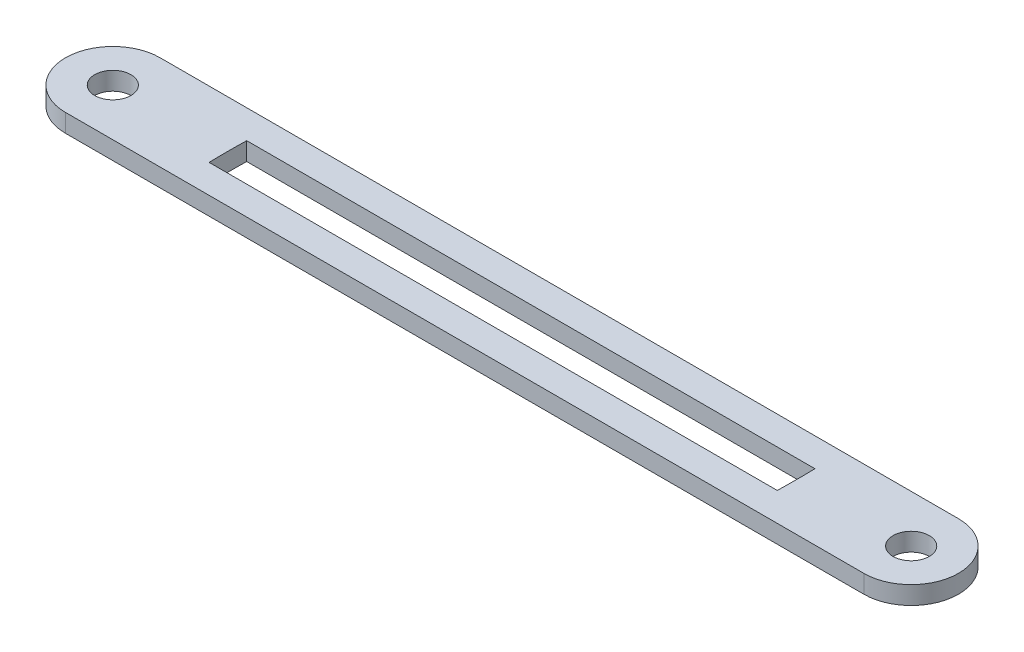
SolidWorks part; units mm, degrees
material "6061-T6 (SS)"
ref_plane "Front Plane" through (0, 0, 0) normal (0, 0, 1) x (1, 0, 0)
ref_plane "Top Plane" through (0, 0, 0) normal (0, 1, 0) x (1, 0, 0)
ref_plane "Right Plane" through (0, 0, 0) normal (1, 0, 0) x (0, 0, -1)
sketch "Sketch1" plane through (0, 0, 0) normal (0, 1, 0) x (1, 0, 0)
  line L0 (-35, 0) -> (35, 0) construction
  line L1 (35, 4.15) -> (-35, 4.15)
  line L3 (-35, -4.15) -> (35, -4.15)
  line L4 (24.9073, -1.65) -> (-24.9073, -1.65)
  line L5 (-24.9073, 1.65) -> (24.9073, 1.65)
  line L6 (35, 1.65) -> (-35, 1.65) construction
  line L7 (-35, -1.65) -> (35, -1.65) construction
  circle A0 centre (35, 0) radius 1.5875
  circle A1 centre (-35, 0) radius 1.5875
  arc A2 (-35, 4.15) -> (-35, -4.15) centre (-35, 0) ccw
  arc A3 (35, -4.15) -> (35, 4.15) centre (35, 0) ccw
  circle A4 centre (-9.4564, 0) radius 0.5953 construction
  circle A5 centre (-4.9564, 0) radius 0.5953 construction
  arc A6 (24.9073, 1.65) -> (24.9073, -1.65) centre (-35, 0) cw
  arc A7 (35, -1.65) -> (35, 1.65) centre (35, 0) ccw
  arc A8 (-35, 1.65) -> (-35, -1.65) centre (-35, 0) ccw construction
  arc A9 (-24.9073, 1.65) -> (-24.9073, -1.65) centre (35, 0) ccw
  point P3 (0, 0)
  dimension "D2" = 3.175
  dimension "D3" = 1.1906
  dimension "D4" = 4.5
  dimension "D1" = 70
  dimension "D5" = 2.5
  dimension "D6" = 2.5
  dimension "D7" = 8.3
extrude "Boss-Extrude2" add sketch "Sketch1" along normal mid plane 1.5875
sketch "Sketch2" plane through (0, -0.7937, 0) normal (0, -1, 0) x (-1, 0, 0)
  point P0 (35, 0)
